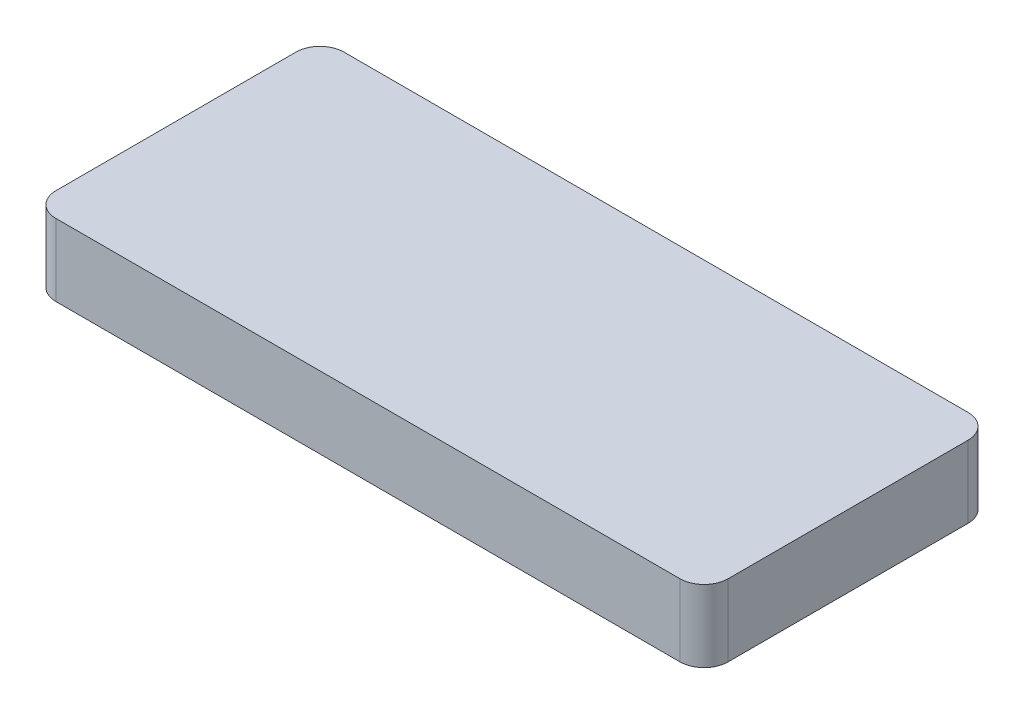
SolidWorks part; units mm, degrees
ref_plane "Front Plane" through (0, 0, 0) normal (0, 0, 1) x (1, 0, 0)
ref_plane "Top Plane" through (0, 0, 0) normal (0, 1, 0) x (1, 0, 0)
ref_plane "Right Plane" through (0, 0, 0) normal (1, 0, 0) x (0, 0, -1)
sketch "Sketch1" plane through (0, 0, 0) normal (0, 1, 0) x (1, 0, 0)
  line L1 (-70, -30) -> (70, -30)
  line L2 (-70, -30) -> (-70, 30)
  line L3 (-70, 30) -> (70, 30)
  line L4 (70, -30) -> (70, 30)
  line L5 (-70, -30) -> (70, 30) construction
  line L6 (-70, 30) -> (70, -30) construction
  point P0 (0, 0)
  dimension "D1" = 140
  dimension "D2" = 60
extrude "Boss-Extrude1" add sketch "Sketch1" along normal blind 15
fillet "Fillet1" radius 5 4 edges at (70, 7.5, -30) (70, 7.5, 30) (-70, 7.5, 30) (-70, 7.5, -30)
